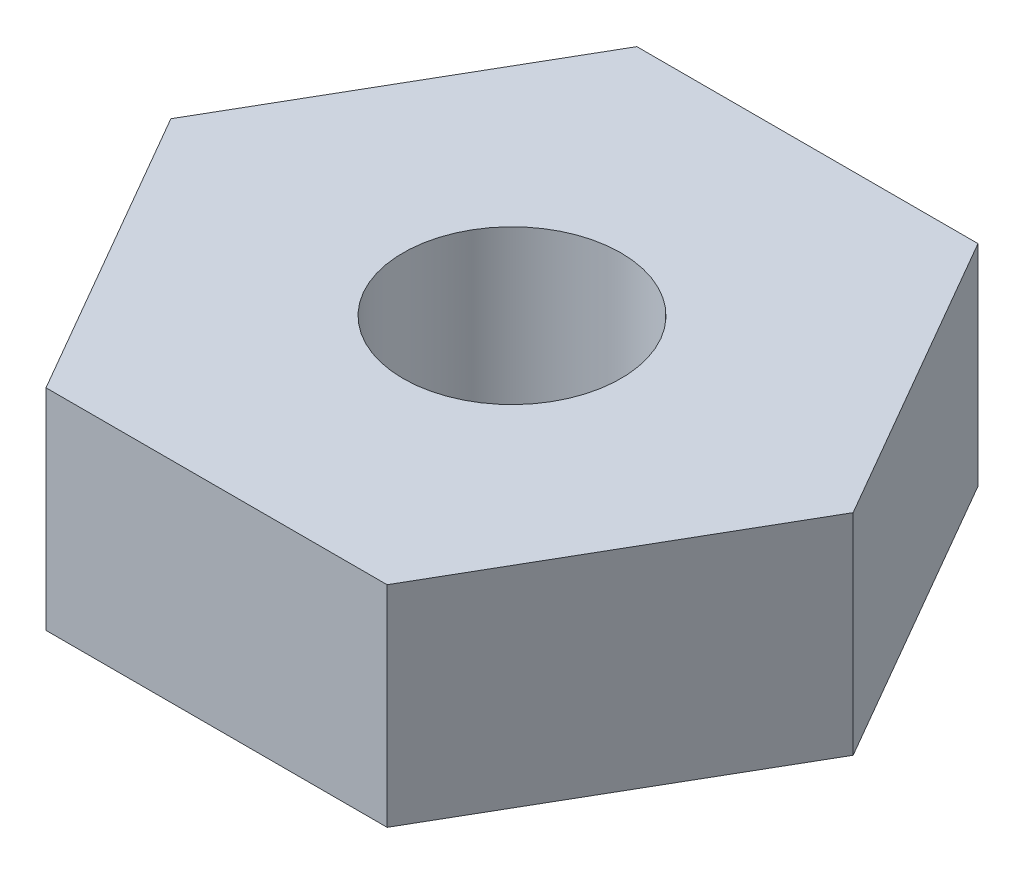
SolidWorks part; units mm, degrees
ref_plane "Front Plane" through (0, 0, 0) normal (0, 0, 1) x (1, 0, 0)
ref_plane "Top Plane" through (0, 0, 0) normal (0, 1, 0) x (1, 0, 0)
ref_plane "Right Plane" through (0, 0, 0) normal (1, 0, 0) x (0, 0, -1)
sketch "Sketch1" plane through (0, 0, 0) normal (0, 1, 0) x (1, 0, 0)
  line L1 (-2.2474, 3.8925) -> (-4.4947, 0)
  line L2 (-4.4947, 0) -> (-2.2474, -3.8926)
  line L3 (-2.2474, -3.8926) -> (2.2474, -3.8926)
  line L4 (2.2474, -3.8926) -> (4.4947, 0)
  line L5 (4.4947, 0) -> (2.2474, 3.8925)
  line L6 (2.2474, 3.8925) -> (-2.2474, 3.8925)
  circle A0 centre (0, 0) radius 3.8925 construction
  dimension "D1" = 7.7851
extrude "Boss-Extrude1" add sketch "Sketch1" along normal blind 2.7686
sketch "Sketch2" plane through (0, 0, 0) normal (0, 1, 0) x (1, 0, 0)
  circle A0 centre (0, 0) radius 1.4351
  dimension "D1" = 2.8702
extrude "Cut-Extrude2" cut sketch "Sketch2" along normal through all
